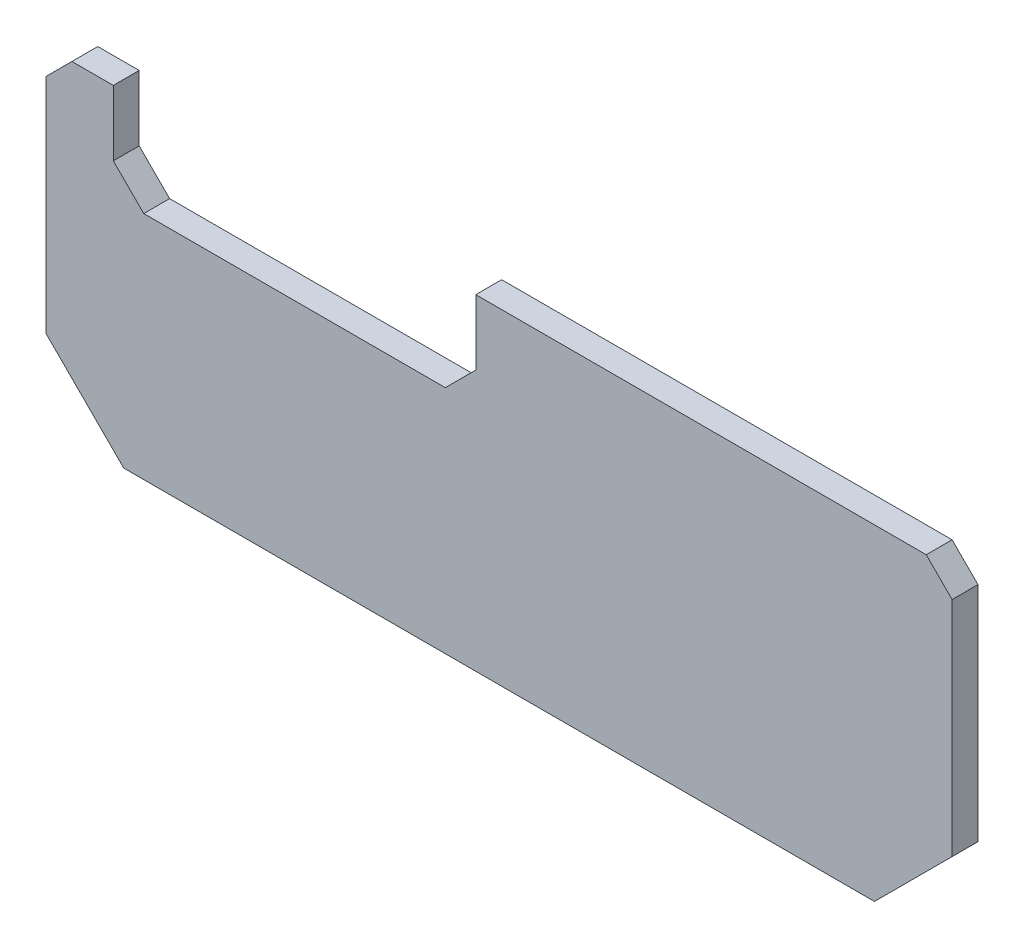
SolidWorks part; units mm, degrees
ref_plane "前视基准面" through (0, 0, 0) normal (0, 0, 1) x (1, 0, 0)
ref_plane "上视基准面" through (0, 0, 0) normal (0, 1, 0) x (1, 0, 0)
ref_plane "右视基准面" through (0, 0, 0) normal (1, 0, 0) x (0, 0, -1)
other "Configuration Table"
sketch "草图1" plane through (0, 0, 0) normal (0, 0, 1) x (1, 0, 0)
  line L0 (-87.5, 42.864) -> (-87.5, 35.8431) construction
  line L1 (-87.5, 56) -> (87.5, 56)
  line L2 (-87.5, 56) -> (-87.5, -7)
  line L3 (-87.5, -7) -> (87.5, -7)
  line L4 (87.5, 56) -> (87.5, -7)
  line L5 (74.364, 56) -> (-74.364, 56) construction
  line L6 (87.5, 35.8431) -> (87.5, 42.864) construction
  line L7 (77, 0) -> (-77, 0) construction
  dimension "D1" = 7
extrude "凸台-拉伸1" add sketch "草图1" along normal blind 5
sketch "草图2" plane through (0, 0, 5) normal (0, 0, 1) x (1, 0, 0)
  line L19 (-74.5, 56) -> (-4.5, 56)
  line L24 (-4.5, 43.3787) -> (-4.5, 56)
  line L25 (-10.3787, 37.5) -> (-4.5, 43.3787)
  line L26 (-68.6213, 37.5) -> (-10.3787, 37.5)
  line L27 (-74.5, 56) -> (-74.5, 43.3787)
  line L28 (-74.5, 43.3787) -> (-68.6213, 37.5)
  line L29 (-4.5, 43.3787) -> (-4.5, 56)
  line L30 (-10.3787, 37.5) -> (-4.5, 43.3787)
  line L31 (-68.6213, 37.5) -> (-10.3787, 37.5)
  line L32 (-74.5, 56) -> (-74.5, 43.3787)
  line L33 (-74.5, 43.3787) -> (-68.6213, 37.5)
  dimension "D1" = 1.5
extrude "切除-拉伸1" cut sketch "草图2" against normal up to next
chamfer "倒角1" distance 15 angle 45 2 edges at (87.5, -7, 2.5) (-87.5, -7, 2.5)
chamfer "倒角2" distance 5 angle 45 2 edges at (87.5, 56, 2.5) (-87.5, 56, 2.5)
